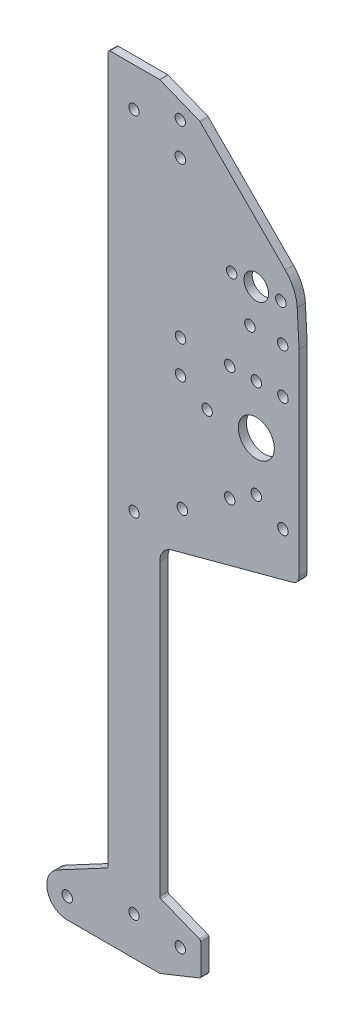
SolidWorks part; units mm, degrees
ref_plane "Front Plane" through (0, 0, 0) normal (0, 0, 1) x (1, 0, 0)
ref_plane "Top Plane" through (0, 0, 0) normal (0, 1, 0) x (1, 0, 0)
ref_plane "Right Plane" through (0, 0, 0) normal (1, 0, 0) x (0, 0, -1)
sketch "Sketch1" plane through (0, 0, 0) normal (0, 0, 1) x (1, 0, 0)
  line L1 (-10, 150) -> (10, 150)
  line L2 (-10, 150) -> (-10, -150)
  line L3 (-10, -150) -> (10, -150)
  line L4 (10, 150) -> (10, -150)
  line L5 (-10, 150) -> (10, -150) construction
  line L6 (-10, -150) -> (10, 150) construction
  point P0 (0, 0)
  dimension "D1" = 300
  dimension "20mm" = 20
extrude "Boss-Extrude1" add sketch "Sketch1" along normal blind 3.175
sketch "Sketch2" plane through (0, 0, 3.175) normal (0, 0, 1) x (1, 0, 0)
  line L0 (10, 150) -> (25.875, 143.65)
  line L1 (25.875, 143.65) -> (25.875, 124.6)
  line L2 (25.875, 124.6) -> (10, 118.25)
  line L3 (10, -150) -> (10, 150) construction
  line L4 (10, 118.25) -> (10, 150)
  line L5 (10, 150) -> (-10, 150) construction
  line L6 (-10, 0) -> (10, 0) construction
  line L7 (-10, 150) -> (-10, -150) construction
  line L8 (10, -118.25) -> (10, -150)
  line L9 (25.875, -124.6) -> (10, -118.25)
  line L10 (25.875, -143.65) -> (25.875, -124.6)
  line L11 (10, -150) -> (25.875, -143.65)
  line L12 (17.9375, 140.475) -> (17.9375, 127.775) construction
  line L13 (17.9375, -127.775) -> (17.9375, -140.475) construction
  circle A1 centre (17.9375, 127.775) radius 5 construction
  circle A2 centre (17.9375, 140.475) radius 2
  circle A4 centre (17.9375, -127.775) radius 5 construction
  circle A5 centre (17.9375, -127.775) radius 2
  circle A6 centre (17.9375, 134.125) radius 2 construction
  circle A7 centre (17.9375, -134.125) radius 2 construction
  circle A8 centre (17.9375, 127.775) radius 2.032
  circle A9 centre (17.9375, -140.475) radius 2
  point P3 (25.875, 134.125)
  point P8 (10, 134.125)
  point P13 (17.9375, 121.425)
  point P31 (25.875, -134.125)
  dimension "D3" = 4
  dimension "D4" = 10
  dimension "D7" = 4.064
  dimension "D1" = 15.875
  dimension "2.5" = 31.75
  dimension "D2" = 19.05
  dimension "D5" = 9.525
  dimension "D6" = 9.525
  dimension "D8" = 12.7
extrude "Boss-Extrude2" add sketch "Sketch2" against normal up to surface (3.175 mm away) up to face at (0, 0, 0)
sketch "Sketch4" plane through (0, 0, 3.175) normal (0, 0, 1) x (1, 0, 0)
  line L0 (0, 150) -> (0, 135) construction
  line L2 (0, 135) -> (0, 0) construction
  line L3 (0, 0) -> (0, -135) construction
  line L4 (0, -135) -> (0, -150) construction
  line L6 (10, 150) -> (-10, 150) construction
  line L7 (-10, -150) -> (10, -150) construction
  circle A0 centre (0, -135) radius 2
  circle A1 centre (0, 0) radius 2
  circle A2 centre (0, 135) radius 2
  dimension "D4" = 4
  dimension "D1" = 15
  dimension "D2" = 135
  dimension "D3" = 135
extrude "Cut-Extrude1" cut sketch "Sketch4" against normal through all
sketch "Sketch5" plane through (0, 0, 3.175) normal (0, 0, 1) x (1, 0, 0)
  line L0 (-10, 111.9) -> (-41.75, 118.25)
  line L1 (-10, 150) -> (-10, -150) construction
  line L2 (-41.75, 118.25) -> (-41.75, 137.3)
  line L3 (-41.75, 137.3) -> (-10, 137.3)
  line L4 (-10, 137.3) -> (-10, 111.9)
  line L5 (10, 150) -> (-10, 150) construction
  line L6 (-41.75, 133.3313) -> (-37.7813, 133.3313) construction
  line L7 (-13.9688, 133.3313) -> (-10, 133.3313) construction
  line L8 (-10, -150) -> (-25.875, -150)
  line L9 (-29.6103, -135.0588) -> (-10, -124.6)
  line L10 (-10, -124.6) -> (-10, -150)
  circle A0 centre (-13.9688, 133.3313) radius 2.032
  circle A1 centre (-13.9688, 122.2188) radius 2.032
  circle A2 centre (-37.7813, 133.3313) radius 2.032
  circle A3 centre (-37.7813, 122.2188) radius 2.032
  arc A4 (-25.875, -150) -> (-29.6103, -135.0588) centre (-25.875, -142.0625) cw
  circle A5 centre (-25.875, -142.0625) radius 2.032
  point P24 (-25.875, 137.3)
  dimension "D5" = 4.064
  dimension "D9" = 4.064
  dimension "D10" = 7.9375
  dimension "D1" = 12.7
  dimension "D2" = 19.05
  dimension "D3" = 25.4
  dimension "D4" = 31.75
  dimension "D6" = 11.1125
  dimension "D7" = 23.8125
  dimension "D8" = 3.9688
  dimension "D11" = 25.4
extrude "Boss-Extrude3" [suppressed] add sketch "Sketch5" against normal up to surface (1.5875 mm away)
fillet "Fillet3" [suppressed] radius 1.5875
sketch "Sketch6" plane through (0, 0, 3.175) normal (0, 0, 1) x (1, 0, 0)
  line L0 (-10, -124.6) -> (-10, -150) construction
  line L1 (-10, -150) -> (-25.875, -150) construction
  line L2 (-29.6103, -135.0588) -> (-10, -124.6) construction
  line L3 (-10, -124.6) -> (-10, -150)
  line L4 (-10, -150) -> (-25.875, -150)
  line L5 (-29.6103, -135.0588) -> (-10, -124.6)
  circle A0 centre (-25.875, -142.0625) radius 2.032 construction
  arc A1 (-29.6103, -135.0588) -> (-25.875, -150) centre (-25.875, -142.0625) ccw construction
  circle A2 centre (-25.875, -142.0625) radius 2.032
  arc A3 (-29.6103, -135.0588) -> (-25.875, -150) centre (-25.875, -142.0625) ccw
extrude "Boss-Extrude4" add sketch "Sketch6" against normal up to vertex (3.175 mm away)
fillet "Fillet4" radius 0.7937 8 edges at (10, 118.25, 1.5875) (25.875, 124.6, 1.5875) (-10, 150, 1.5875) (25.875, 143.65, 1.5875) (-10, -124.6, 1.5875) (10, -118.25, 1.5875) (25.875, -124.6, 1.5875) (25.875, -143.65, 1.5875)
fillet "Fillet5" [suppressed] radius 1.5875
sketch "Sketch7" plane through (0, 0, 0) normal (0, 0, -1) x (-1, 0, 0)
  line L0 (-25.5339, 143.7646) -> (-63.6339, 117.3145)
  line L1 (-63.975, 116.6625) -> (-63.975, 10.1095)
  line L2 (-61.6218, 7.0427) -> (-10, -6.7893)
  line L4 (-10, -6.7893) -> (-10, 117.7126)
  line L5 (-25.875, 143.1126) -> (-25.875, 125.1374) construction
  line L6 (-25.376, 124.4004) -> (-10.499, 118.4496) construction
  line L7 (-25.875, 143.1126) -> (-25.875, 125.1374)
  line L8 (-25.376, 124.4004) -> (-10.499, 118.4496)
  line L9 (-10, 150) -> (9.2063, 150) construction
  line L10 (-10, 150) -> (9.2063, 150) construction
  line L11 (-47.4015, 45.225) -> (-47.4015, 48.4) construction
  line L12 (-37.0827, 23) -> (-57.7202, 23) construction
  line L13 (-37.0827, 23) -> (-37.0827, 67.45) construction
  line L14 (-37.0827, 67.45) -> (-57.7202, 67.45) construction
  line L15 (-57.7202, 23) -> (-57.7202, 67.45) construction
  line L16 (-37.0827, 23) -> (-57.7202, 67.45) construction
  line L17 (-37.0827, 67.45) -> (-57.7202, 23) construction
  line L18 (-47.4015, 99.2) -> (-47.4015, 48.4) construction
  line L19 (-10, -117.7126) -> (-10, 117.7126) construction
  arc A0 (-63.6339, 117.3145) -> (-63.975, 116.6625) centre (-63.1812, 116.6625) ccw
  arc A1 (-63.975, 10.1095) -> (-61.6218, 7.0427) centre (-60.8, 10.1095) ccw
  arc A2 (-25.376, 143.8496) -> (-25.875, 143.1126) centre (-25.0813, 143.1126) ccw construction
  arc A3 (-25.875, 125.1374) -> (-25.376, 124.4004) centre (-25.0813, 125.1374) ccw construction
  arc A4 (-10, 117.7126) -> (-10.499, 118.4496) centre (-10.7937, 117.7126) ccw construction
  arc A5 (-25.5339, 143.7646) -> (-25.875, 143.1126) centre (-25.0813, 143.1126) ccw
  arc A6 (-25.875, 125.1374) -> (-25.376, 124.4004) centre (-25.0813, 125.1374) ccw
  arc A7 (-10, 117.7126) -> (-10.499, 118.4496) centre (-10.7937, 117.7126) ccw
  arc A8 (10, 149.2063) -> (9.2063, 150) centre (9.2063, 149.2063) ccw construction
  circle A9 centre (-47.4015, 99.2) radius 4.7625
  circle A10 centre (-47.4015, 48.4) radius 6.985
  circle A11 centre (-57.7202, 67.45) radius 2.032
  circle A12 centre (-57.7202, 23) radius 2.032
  circle A13 centre (-37.0827, 23) radius 2.032
  circle A14 centre (-37.0827, 67.45) radius 2.032
  circle A15 centre (-18.7312, 10.3) radius 2.032
  point P32 (-47.4015, 45.225)
  dimension "D4" = 9.525
  dimension "D6" = 13.97
  dimension "D11" = 4.064
  dimension "D15" = 3.175
  dimension "D1" = 38.1
  dimension "D2" = 106.553
  dimension "D3" = 16.5735
  dimension "D5" = 50.8
  dimension "D7" = 3.175
  dimension "D8" = 44.45
  dimension "D9" = 50.8
  dimension "D10" = 20.6375
  dimension "D12" = 75
  dimension "D13" = 139.7
  dimension "D14" = 33.3375
extrude "Boss-Extrude5" add sketch "Sketch7" against normal up to surface (3.175 mm away) up to face at (2, -135, 3.175)
sketch "Sketch8" plane through (0, 0, 3.175) normal (0, 0, 1) x (1, 0, 0)
  line L0 (47.4015, 48.4) -> (47.4015, 67.45) construction
  line L1 (47.4015, 48.4) -> (28.3515, 48.4) construction
  line L2 (47.4015, 48.4) -> (47.4015, 29.35) construction
  line L3 (47.4015, 99.2) -> (56.9265, 99.2) construction
  line L4 (47.4015, 99.2) -> (37.8765, 99.2) construction
  line L5 (18.0327, 67.45) -> (18.0327, 54.75) construction
  circle A0 centre (47.4015, 67.45) radius 2.032
  circle A1 centre (28.3515, 48.4) radius 2.032
  circle A2 centre (47.4015, 29.35) radius 2.032
  circle A3 centre (57.7202, 67.45) radius 2.032 construction
  circle A4 centre (56.9265, 99.2) radius 2.032
  circle A5 centre (37.8765, 99.2) radius 2.032
  circle A6 centre (18.0327, 54.75) radius 2.032
  circle A7 centre (18.0327, 67.45) radius 2.032
  dimension "D2" = 9.525
  dimension "D1" = 19.05
  dimension "D3" = 12.7
  dimension "D4" = 6.35
  dimension "D5" = 10.3187
extrude "Cut-Extrude2" cut sketch "Sketch8" against normal through all
sketch "Sketch9" plane through (0, 0, 0) normal (0, 0, -1) x (-1, 0, 0)
  line L0 (-25.6447, 143.6716) -> (-58.6715, 110.3805)
  line L2 (-63.975, 86.5) -> (-63.2541, 100.0438)
  line L3 (-63.975, 86.5) -> (-63.975, 116.6625)
  line L4 (-25.5339, 143.7646) -> (-63.6339, 117.3145) construction
  line L5 (-25.5339, 143.7646) -> (-63.6339, 117.3145)
  line L6 (-63.975, 116.6625) -> (-63.975, 10.1095) construction
  arc A0 (-25.376, 143.8496) -> (-25.5339, 143.7646) centre (-25.0813, 143.1126) ccw construction
  arc A1 (-25.5339, 143.7646) -> (-25.6447, 143.6716) centre (-25.0813, 143.1126) ccw
  arc A2 (-58.6715, 110.3805) -> (-63.2541, 100.0438) centre (-47.4015, 99.2) ccw
  arc A4 (-63.6339, 117.3145) -> (-63.975, 116.6625) centre (-63.1812, 116.6625) ccw construction
  arc A5 (-63.6339, 117.3145) -> (-63.975, 116.6625) centre (-63.1812, 116.6625) ccw
  circle A6 centre (-57.7202, 67.45) radius 2.032 construction
  dimension "D1" = 15.875
  dimension "D2" = 19.05
extrude "Cut-Extrude3" cut sketch "Sketch9" against normal through all
sketch "Sketch10" plane through (0, 0, 0) normal (0, 0, -1) x (-1, 0, 0)
  line L0 (-57.625, 84.9125) -> (-44.925, 84.9125) construction
  line L1 (-63.975, 86.5) -> (-63.975, 10.1095) construction
  circle A0 centre (-57.625, 84.9125) radius 2.032
  circle A1 centre (-44.925, 84.9125) radius 2.032
  circle A2 centre (-57.7202, 67.45) radius 2.032 construction
  point P6 (-47.4015, 67.45)
  dimension "D1" = 12.7
  dimension "D2" = 17.4625
  dimension "D3" = 6.35
extrude "Cut-Extrude4" cut sketch "Sketch10" against normal through all
fillet "Fillet6" radius 6.35 1 edges at (10, -6.7893, 1.5875)
sketch "Sketch11" plane through (0, 0, 3.175) normal (0, 0, 1) x (1, 0, 0)
  line L0 (10, -117.7126) -> (10, -150)
  line L1 (10, -150) -> (25.376, -143.8496) construction
  line L2 (25.875, -143.1126) -> (25.875, -125.1374) construction
  line L3 (25.875, -143.1126) -> (25.875, -125.1374)
  line L4 (10, -150) -> (25.376, -143.8496)
  arc A0 (10, -117.7126) -> (10.499, -118.4496) centre (10.7937, -117.7126) ccw construction
  arc A1 (25.875, -125.1374) -> (25.376, -124.4004) centre (25.0813, -125.1374) ccw construction
  arc A2 (25.376, -143.8496) -> (25.875, -143.1126) centre (25.0813, -143.1126) ccw construction
  arc A3 (10, -117.7126) -> (10.499, -118.4496) centre (10.7937, -117.7126) ccw
  arc A4 (25.875, -125.1374) -> (25.376, -124.4004) centre (25.0813, -125.1374) ccw
  arc A5 (25.376, -143.8496) -> (25.875, -143.1126) centre (25.0813, -143.1126) ccw
  point P3 (10, -150)
extrude "Cut-Extrude5" cut sketch "Sketch11" against normal through all and the other way through all
sketch "Sketch12" plane through (0, 0, 3.175) normal (0, 0, 1) x (1, 0, 0)
  line L0 (10, -150) -> (25.875, -143.65)
  line L1 (25.875, -143.65) -> (25.875, -130.95)
  line L2 (25.875, -130.95) -> (10, -124.6)
  line L3 (10, -150) -> (10, -11.6618) construction
  line L4 (10, -124.6) -> (10, -150)
  line L5 (17.9375, -127.775) -> (17.9375, -146.825) construction
  circle A0 centre (17.9375, -137.3) radius 2.032
  dimension "D4" = 4.064
  dimension "D1" = 25.4
  dimension "D2" = 12.7
  dimension "D3" = 15.875
extrude "Boss-Extrude6" add sketch "Sketch12" against normal up to surface (3.175 mm away) up to face at (16.6992, 10.3, 0)
fillet "Fillet7" radius 0.7937 4 edges at (10, -150, 1.5875) (25.875, -143.65, 1.5875) (25.875, -130.95, 1.5875) (10, -124.6, 1.5875)
